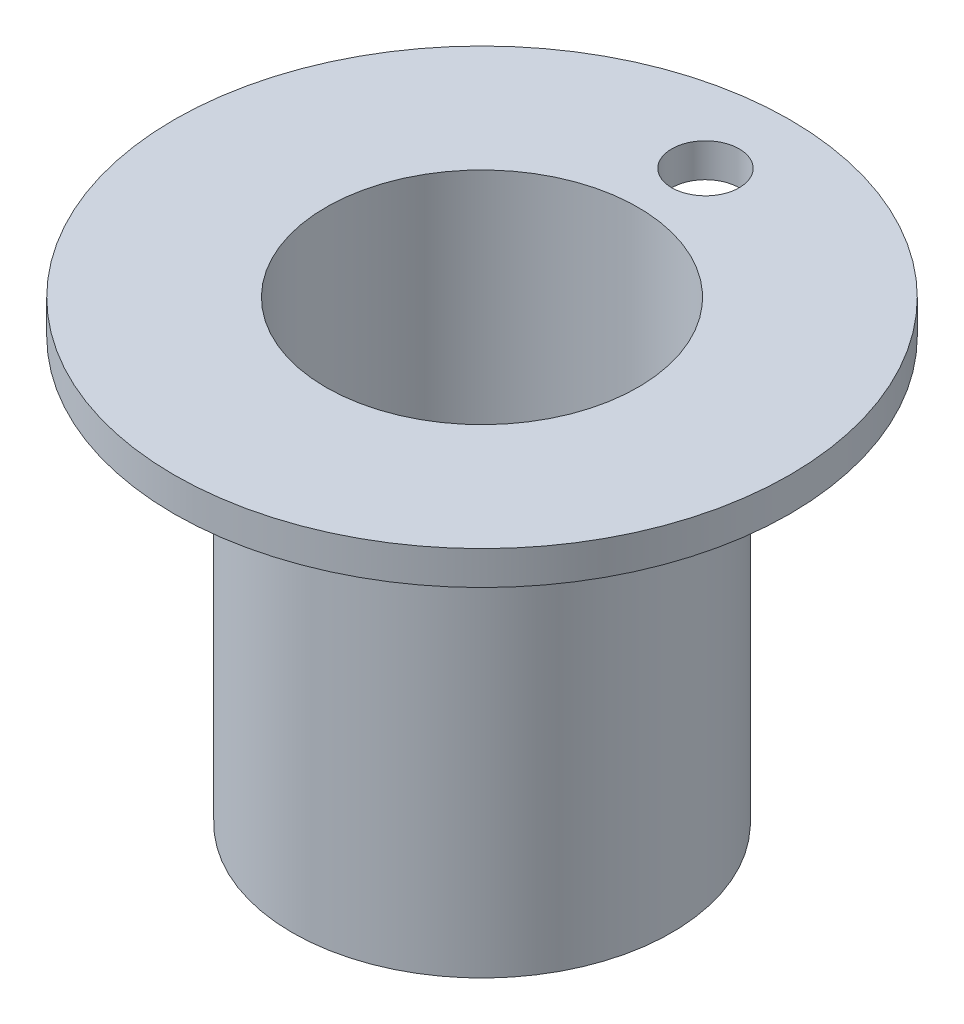
SolidWorks part; units mm, degrees
ref_plane "Front Plane" through (0, 0, 0) normal (0, 0, 1) x (1, 0, 0)
ref_plane "Top Plane" through (0, 0, 0) normal (0, 1, 0) x (1, 0, 0)
ref_plane "Right Plane" through (0, 0, 0) normal (1, 0, 0) x (0, 0, -1)
sketch "Sketch1" plane through (0, 0, 0) normal (0, 1, 0) x (1, 0, 0)
  circle A0 centre (0, 0) radius 9.25
  circle A1 centre (0, 0) radius 11.25
  dimension "D1" = 18.5
  dimension "D2" = 2
extrude "Boss-Extrude1" add sketch "Sketch1" along normal blind 25
sketch "Sketch2" plane through (0, 25, 0) normal (0, 1, 0) x (1, 0, 0)
  circle A0 centre (0, 0) radius 9.25 construction
  circle A1 centre (0, 0) radius 9.25
  circle A2 centre (0, 0) radius 18.25
  circle A3 centre (0, 0) radius 11.25 construction
  dimension "D1" = 7
extrude "Boss-Extrude2" add sketch "Sketch2" along normal blind 2
sketch "Sketch3" plane through (0, 27, 0) normal (0, 1, 0) x (1, 0, 0)
  circle A0 centre (0, 13.25) radius 2
  circle A1 centre (0, 0) radius 11.25 construction
  dimension "D1" = 4
extrude "Cut-Extrude1" cut sketch "Sketch3" against normal blind 2
